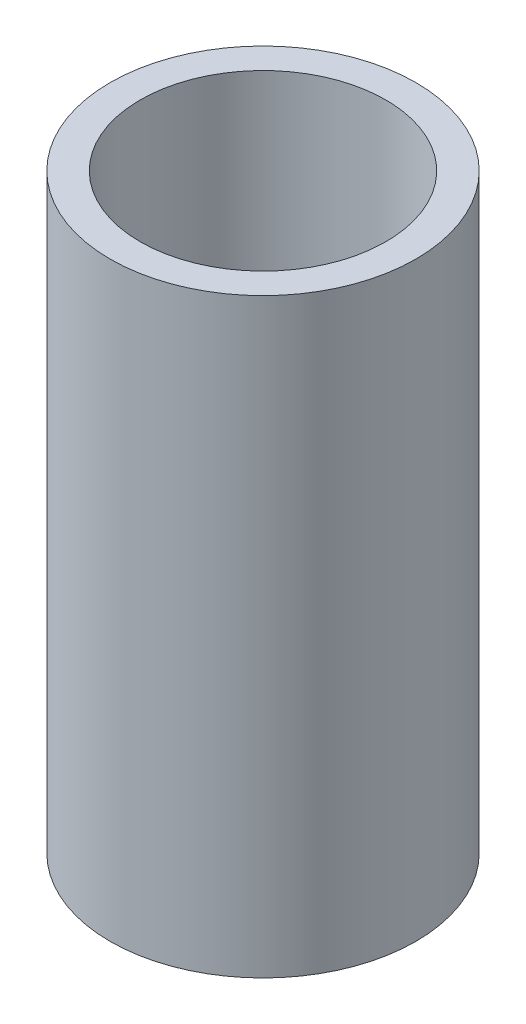
SolidWorks part; units mm, degrees
ref_plane "Front Plane" through (0, 0, 0) normal (0, 0, 1) x (1, 0, 0)
ref_plane "Top Plane" through (0, 0, 0) normal (0, 1, 0) x (1, 0, 0)
ref_plane "Right Plane" through (0, 0, 0) normal (1, 0, 0) x (0, 0, -1)
sketch "Sketch2" plane through (0, 0, 0) normal (0, 1, 0) x (1, 0, 0)
  circle A0 centre (0, 0) radius 10.395
  circle A1 centre (0, 0) radius 12.935
  dimension "D1" = 2.54
extrude "Boss-Extrude1" add sketch "Sketch2" along normal blind 50
